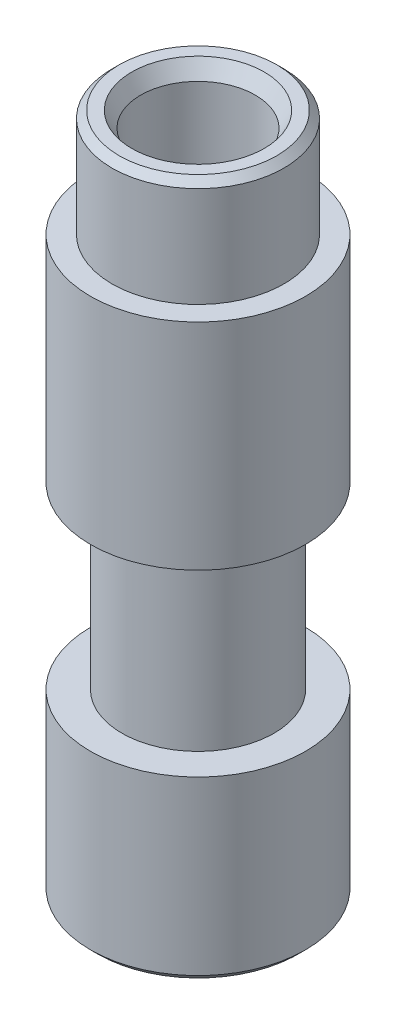
SolidWorks part; units mm, degrees
material "AISI 304"
ref_plane "Front Plane" through (0, 0, 0) normal (0, 0, 1) x (1, 0, 0)
ref_plane "Top Plane" through (0, 0, 0) normal (0, 1, 0) x (1, 0, 0)
ref_plane "Right Plane" through (0, 0, 0) normal (1, 0, 0) x (0, 0, -1)
sketch "Sketch1" plane through (0, 0, 0) normal (0, 1, 0) x (1, 0, 0)
  circle A0 centre (0, 0) radius 3
  dimension "D1" = 6
extrude "Boss-Extrude1" [suppressed] add sketch "Sketch1" along normal blind 7
cosmetic thread "Rosca cosmética1" [suppressed] parameters "D2"=5
sketch "Sketch2" [suppressed] plane through (0, 7, 0) normal (0, 1, 0) x (1, 0, 0)
  circle A0 centre (0, 0) radius 2.1
  dimension "D1" = 4.2
extrude "Boss-Extrude2" [suppressed] add sketch "Sketch2" along normal blind 2
sketch "Sketch3" [suppressed] plane through (0, 9, 0) normal (0, 1, 0) x (1, 0, 0)
  circle A0 centre (0, 0) radius 3
  dimension "D1" = 6
extrude "Boss-Extrude3" [suppressed] add sketch "Sketch3" along normal blind 6
cosmetic thread "Rosca cosmética2" parameters "D2"=5
sketch "Sketch4" [suppressed] plane through (0, 15, 0) normal (0, 1, 0) x (1, 0, 0)
  circle A0 centre (0, 0) radius 1.6
  dimension "D1" = 3.2
extrude "Cut-Extrude1" [suppressed] cut sketch "Sketch4" against normal through all
sketch "Croquis1" [suppressed] plane through (0, 15, 0) normal (0, 1, 0) x (1, 0, 0)
  circle A0 centre (0, 0) radius 2.4
  circle A1 centre (0, 0) radius 1.6
  circle A2 centre (0, 0) radius 1.6 construction
  dimension "D1" = 4.8
extrude "Saliente-Extruir1" [suppressed] add sketch "Croquis1" along normal blind 3
chamfer "Chaflán1" [suppressed] distance 0.2 angle 45
chamfer "Chaflán2" [suppressed] distance 0.2 angle 45
chamfer "Chaflán3" [suppressed] distance 0.25 angle 60
sketch "Croquis2" [suppressed] plane through (0, 0, 0) normal (0, 0, 1) x (1, 0, 0)
  line L0 (0, 17.8) -> (0, 0) construction
  line L1 (3, 11) -> (2.2, 11)
  line L2 (3, 11) -> (3, 5)
  line L3 (3, 5) -> (2.2, 5)
  line L4 (2.2, 11) -> (2.2, 5)
  line L5 (-3, 11) -> (-2.2, 11)
  line L6 (-3, 11) -> (-3, 5)
  line L7 (-3, 5) -> (-2.2, 5)
  line L8 (-2.2, 11) -> (-2.2, 5)
  line L9 (-2.4, 17.8) -> (2.4, 17.8) construction
  line L10 (-2.1, 8) -> (2.1, 8) construction
  line L11 (-2.1, 9) -> (-2.1, 7) construction
  line L12 (2.1, 7) -> (2.1, 9) construction
  line L13 (-3, 15) -> (-3, 9) construction
  line L14 (3, 9) -> (3, 15) construction
  dimension "D1" = 4.4
  dimension "D2" = 2.2
  dimension "D3" = 6
  dimension "D4" = 3
extrude "Cortar-Extruir1" [suppressed] cut sketch "Croquis2" against normal through all and the other way through all
sketch "Croquis3" plane through (0, 0, 0) normal (0, 0, 1) x (1, 0, 0)
  line L0 (-1.6, 0) -> (-1.6, 19)
  line L1 (-1.6, 19) -> (-2.4, 19)
  line L2 (-2.4, 19) -> (-2.4, 16)
  line L3 (-2.4, 16) -> (-3, 16)
  line L4 (-3, 16) -> (-3, 10)
  line L5 (-3, 10) -> (-2.125, 10)
  line L6 (-2.125, 10) -> (-2.125, 5)
  line L7 (-2.125, 5) -> (-3, 5)
  line L8 (-3, 5) -> (-3, 0)
  line L9 (-3, 0) -> (-1.6, 0)
  line L10 (0, 0) -> (0, 18.5179) construction
  dimension "D1" = 3.2
  dimension "D2" = 6
  dimension "D3" = 4.8
  dimension "D4" = 19
  dimension "D5" = 5
  dimension "D6" = 3
  dimension "D7" = 5
  dimension "D8" = 4.25
revolve "Revolución1" add sketch "Croquis3" angle 360 about L10
cosmetic thread "Rosca cosmética4" parameters "D2"=4.891
chamfer "Chaflán4" distance 0.2 angle 45 2 edges at (0, 19, -2.4) (0, 0, -3)
chamfer "Chaflán5" distance 0.25 angle 60 1 edges at (0, 19, -1.6)
sketch "Croquis4" [suppressed] plane through (0, 0, 0) normal (0, 0, 1) x (1, 0, 0)
  line L0 (2.1, 4) -> (2.1, 10) construction
  line L1 (2.1, 7) -> (2.25, 7)
  line L2 (2.1, 7) -> (2.1, 4)
  line L3 (2.1, 4) -> (2.25, 4)
  line L4 (2.25, 7) -> (2.25, 4)
  line L5 (0, 0) -> (0, 18.281) construction
  line L6 (3, 4) -> (-3, 4) construction
  dimension "D1" = 3
  dimension "D2" = 0.15
revolve "Revolución2" [suppressed] add sketch "Croquis4" angle 360 about L5
equation "\"D2@Croquis2\"=\"D1@Croquis2\"/2"
equation "\"D4@Croquis2\"=\"D3@Croquis2\"/2"
